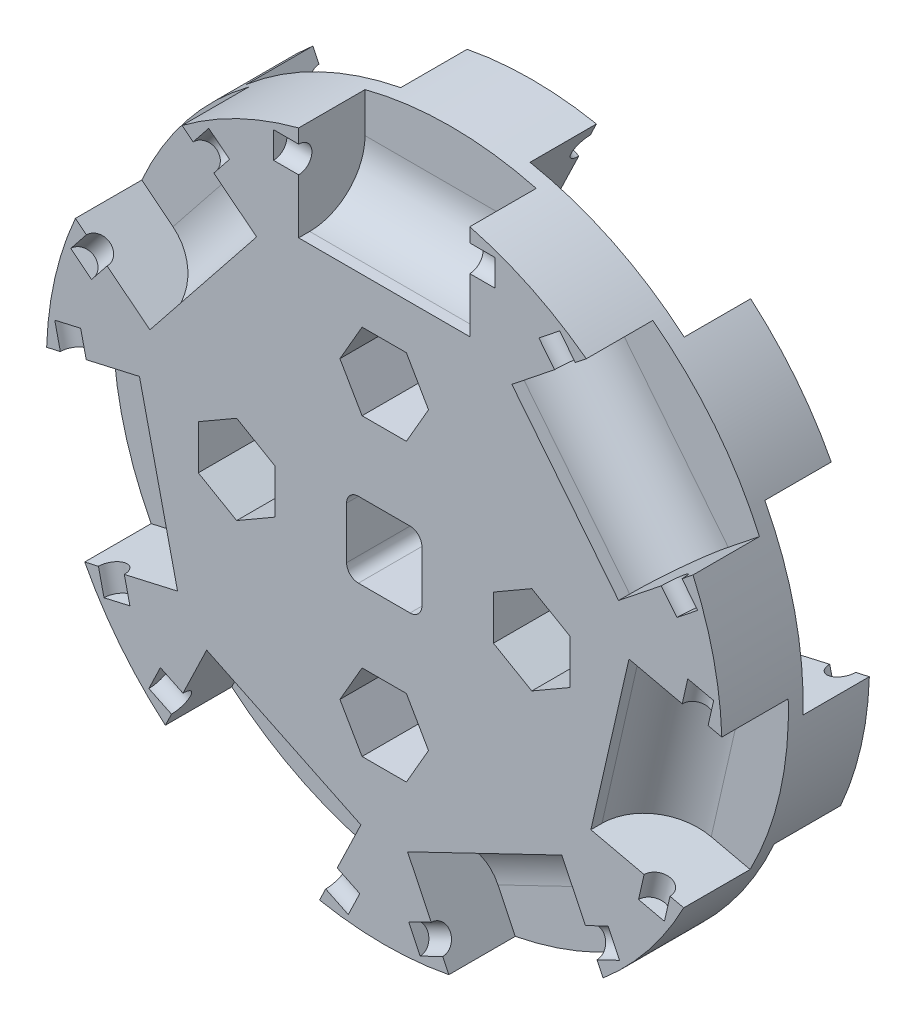
SolidWorks part; units mm, degrees
other "Markup1"
sketch "Sketch8" plane through (32.7336, 32.7336, 0) normal (0.5701, 0.1846, 0.8006) x (0.8043, 0.0736, -0.5897)
ref_plane "Front Plane" through (0, 0, 0) normal (0, 0, 1) x (1, 0, 0)
ref_plane "Top Plane" through (0, 0, 0) normal (0, 1, 0) x (1, 0, 0)
ref_plane "Right Plane" through (0, 0, 0) normal (1, 0, 0) x (0, 0, -1)
sketch "Sketch1" plane through (0, 0, 0) normal (0, 0, 1) x (1, 0, 0)
  circle A0 centre (0, 0) radius 29.0703
  dimension "D1" = 58.1406
extrude "Boss-Extrude2" add sketch "Sketch1" against normal blind 6.35
sketch "Sketch2" plane through (0, 0, 0) normal (0, 0, 1) x (1, 0, 0)
  line L1 (-12.7, 29.0703) -> (12.7, 29.0703) construction
  line L2 (-7.366, 30.3403) -> (7.366, 30.3403)
  line L3 (-7.366, 30.3403) -> (-7.366, 19.9263)
  line L4 (-7.366, 19.9263) -> (7.366, 19.9263)
  line L5 (7.366, 30.3403) -> (7.366, 19.9263)
  line L6 (-7.366, 30.3403) -> (7.366, 19.9263) construction
  line L7 (-7.366, 19.9263) -> (7.366, 30.3403) construction
  line L35 (0, 0) -> (0, 29.0703) construction
  circle A1 centre (0, 0) radius 29.0703 construction
  point P10 (0, 25.1333)
  circle M7 centre (0, 0) radius 29.0703
  dimension "D1" = 14.732
  dimension "D2" = 10.414
  dimension "D3" = 1.27
  dimension "D4" = 25.4
extrude "Cut-Extrude2" cut sketch "Sketch2" against normal blind 5.715 contours L5 L3 L4 M7
pattern_circular "CirPattern1" count 7 over 360 about axis through (0, 0, 0) along (0, 0, 1) of "Cut-Extrude2"
ref_plane "Plane1" through (0, 0, 0) normal (1, 0, 0) x (0, 0, -1)
sketch "Sketch4" plane through (0, 0, 0) normal (1, 0, 0) x (0, 0, -1)
  line L0 (5.715, 19.9263) -> (0, 19.9263) construction
  circle A0 centre (0, 25.7683) radius 1.143
  dimension "D1" = 2.286
  dimension "D2" = 5.842
extrude "Cut-Extrude4" cut sketch "Sketch4" against normal mid plane 19.05
pattern_circular "CirPattern2" count 7 over 360 about axis through (0, 0, 0) along (0, 0, 1) of "Cut-Extrude4"
sketch "Sketch5" plane through (0, 0, 0) normal (0, 0, 1) x (1, 0, 0)
  line L1 (-3.2385, -3.2385) -> (3.2385, -3.2385)
  line L2 (-3.2385, -3.2385) -> (-3.2385, 3.2385)
  line L3 (-3.2385, 3.2385) -> (3.2385, 3.2385)
  line L4 (3.2385, -3.2385) -> (3.2385, 3.2385)
  line L5 (-3.2385, -3.2385) -> (3.2385, 3.2385) construction
  line L6 (-3.2385, 3.2385) -> (3.2385, -3.2385) construction
  point P0 (0, 0)
  dimension "D1" = 6.477
extrude "Cut-Extrude5" cut sketch "Sketch5" against normal through all
sketch "Sketch6" plane through (0, 0, -6.35) normal (0, 0, -1) x (-1, 0, 0)
  line L0 (12.7, -3.8128) -> (16.002, -1.9064)
  line L1 (16.002, -1.9064) -> (16.002, 1.9064)
  line L2 (16.002, 1.9064) -> (12.7, 3.8128)
  line L3 (3.8128, 12.7) -> (1.9064, 16.002)
  line L4 (1.9064, 16.002) -> (-1.9064, 16.002)
  line L5 (-1.9064, 16.002) -> (-3.8128, 12.7)
  line L6 (-3.8128, 12.7) -> (-1.9064, 9.398)
  line L7 (-1.9064, 9.398) -> (1.9064, 9.398)
  line L8 (1.9064, 9.398) -> (3.8128, 12.7)
  line L9 (12.7, 3.8128) -> (9.398, 1.9064)
  line L10 (9.398, 1.9064) -> (9.398, -1.9064)
  line L11 (9.398, -1.9064) -> (12.7, -3.8128)
  line L12 (-3.8128, -12.7) -> (-1.9064, -16.002)
  line L13 (-1.9064, -16.002) -> (1.9064, -16.002)
  line L14 (1.9064, -16.002) -> (3.8128, -12.7)
  line L15 (3.8128, -12.7) -> (1.9064, -9.398)
  line L16 (1.9064, -9.398) -> (-1.9064, -9.398)
  line L17 (-1.9064, -9.398) -> (-3.8128, -12.7)
  line L18 (-12.7, 3.8128) -> (-16.002, 1.9064)
  line L19 (-16.002, 1.9064) -> (-16.002, -1.9064)
  line L20 (-16.002, -1.9064) -> (-12.7, -3.8128)
  line L21 (-12.7, -3.8128) -> (-9.398, -1.9064)
  line L22 (-9.398, -1.9064) -> (-9.398, 1.9064)
  line L23 (-9.398, 1.9064) -> (-12.7, 3.8128)
  circle A4 centre (0, 12.7) radius 3.302 construction
  circle A5 centre (12.7, 0) radius 3.302 construction
  circle A6 centre (0, -12.7) radius 3.302 construction
  circle A7 centre (-12.7, 0) radius 3.302 construction
  dimension "D3" = 4
  dimension "D1" = 6.604
  dimension "D2" = 12.7
extrude "Cut-Extrude7" cut sketch "Sketch6" against normal through all
sketch "Sketch9" plane through (0, 0, -6.35) normal (0, 0, -1) x (-1, 0, 0)
  line L0 (3.2385, -3.2385) -> (-3.2385, -3.2385) construction
  line L1 (-3.2385, 3.2385) -> (3.2385, 3.2385)
  line L2 (-3.2385, 3.2385) -> (-3.2385, -3.2385)
  line L3 (-3.2385, -3.2385) -> (3.2385, -3.2385)
  line L4 (3.2385, 3.2385) -> (3.2385, -3.2385)
  line L5 (-3.2385, 3.2385) -> (3.2385, -3.2385) construction
  line L6 (-3.2385, -3.2385) -> (3.2385, 3.2385) construction
  line L7 (12.7, -3.8128) -> (16.002, -1.9064)
  line L8 (3.8128, 12.7) -> (1.9064, 16.002)
  line L9 (1.9064, 16.002) -> (-1.9064, 16.002)
  line L10 (-1.9064, 16.002) -> (-3.8128, 12.7)
  line L11 (-3.8128, 12.7) -> (-1.9064, 9.398)
  line L12 (-1.9064, 9.398) -> (1.9064, 9.398)
  line L13 (1.9064, 9.398) -> (3.8128, 12.7)
  line L14 (16.002, -1.9064) -> (16.002, 1.9064)
  line L15 (16.002, 1.9064) -> (12.7, 3.8128)
  line L16 (12.7, 3.8128) -> (9.398, 1.9064)
  line L17 (9.398, 1.9064) -> (9.398, -1.9064)
  line L18 (9.398, -1.9064) -> (12.7, -3.8128)
  line L19 (-3.8128, -12.7) -> (-1.9064, -16.002)
  line L20 (-1.9064, -16.002) -> (1.9064, -16.002)
  line L21 (1.9064, -16.002) -> (3.8128, -12.7)
  line L22 (3.8128, -12.7) -> (1.9064, -9.398)
  line L23 (1.9064, -9.398) -> (-1.9064, -9.398)
  line L24 (-1.9064, -9.398) -> (-3.8128, -12.7)
  line L25 (-12.7, 3.8128) -> (-16.002, 1.9064)
  line L26 (-16.002, 1.9064) -> (-16.002, -1.9064)
  line L27 (-16.002, -1.9064) -> (-12.7, -3.8128)
  line L28 (-12.7, -3.8128) -> (-9.398, -1.9064)
  line L29 (-9.398, -1.9064) -> (-9.398, 1.9064)
  line L30 (-9.398, 1.9064) -> (-12.7, 3.8128)
  circle A0 centre (0, 0) radius 29.0703
  circle A5 centre (0, 12.7) radius 3.302 construction
  circle A6 centre (12.7, 0) radius 3.302 construction
  circle A7 centre (0, -12.7) radius 3.302 construction
  circle A8 centre (-12.7, 0) radius 3.302 construction
  circle A9 centre (0, 0) radius 29.0703 construction
  dimension "D2" = 12.7
  dimension "D3" = 4
extrude "Boss-Extrude3" add sketch "Sketch9" along normal blind 6.35
sketch "Sketch10" plane through (0, 0, -12.7) normal (0, 0, -1) x (-1, 0, 0)
  line L0 (-25.313, 26.1915) -> (0.087, 26.1915) construction
  line L1 (-2.0091, 21.149) -> (-15.2822, 14.7571)
  line L2 (-2.0091, 21.149) -> (-6.5275, 30.5317)
  line L3 (-6.5275, 30.5317) -> (-19.8006, 24.1398)
  line L4 (-15.2822, 14.7571) -> (-19.8006, 24.1398)
  line L5 (-2.0091, 21.149) -> (-19.8006, 24.1398) construction
  line L6 (-6.5275, 30.5317) -> (-15.2822, 14.7571) construction
  line L7 (0, 0) -> (-12.613, 26.1915) construction
  line L8 (0, 0) -> (0, 40.3277) construction
  circle A2 centre (0, 0) radius 29.0703 construction
  point P8 (-10.9048, 22.6444)
  dimension "D1" = 1.27
  dimension "D2" = 14.732
  dimension "D3" = 10.414
  dimension "D4" = 25.4
  dimension "D5" = 25.714
extrude "Cut-Extrude8" cut sketch "Sketch10" against normal blind 5.715
pattern_circular "CirPattern3" count 7 over 360 about axis through (0, 0, 0) along (0, 0, 1) of "Cut-Extrude8"
ref_plane "Plane2" through (0, 0, 0) normal (-0.901, 0.4339, 0) x (0, 0, -1)
sketch "Sketch11" plane through (0, 0, 0) normal (-0.901, 0.4339, 0) x (0, 0, -1)
  line L5 (6.985, -19.9263) -> (12.7, -19.9263) construction
  line L6 (12.7, -28.1216) -> (12.7, -23.2925) construction
  circle A0 centre (12.7, -25.7683) radius 1.143
  dimension "D1" = 2.286
  dimension "D2" = 5.842
extrude "Cut-Extrude9" cut sketch "Sketch11" against normal mid plane 19.05
pattern_circular "CirPattern4" count 7 over 360 about axis through (0, 0, 0) along (0, 0, 1) of "Cut-Extrude9"
fillet "Fillet1" radius 4.7625 14 edges at (19.4267, 4.4341, -6.985) (15.5791, -12.4238, -6.985) (0.0001, -19.9263, -6.985) (8.6456, 17.953, -6.985) (-19.4267, 4.4339, -6.985) (-15.5789, -12.4239, -6.985) (-19.4267, -4.434, -5.715) (-8.6457, -17.953, -5.715) (8.6457, -17.953, -5.715) (19.4267, -4.434, -5.715) (0, 19.9263, -5.715) (-15.579, 12.4238, -5.715) (-8.6458, 17.9529, -6.985) (15.579, 12.4238, -5.715)
fillet "Fillet2" radius 1.016 4 edges at (3.2385, -3.2385, -6.35) (3.2385, 3.2385, -6.35) (-3.2385, 3.2385, -6.35) (-3.2385, -3.2385, -6.35)
